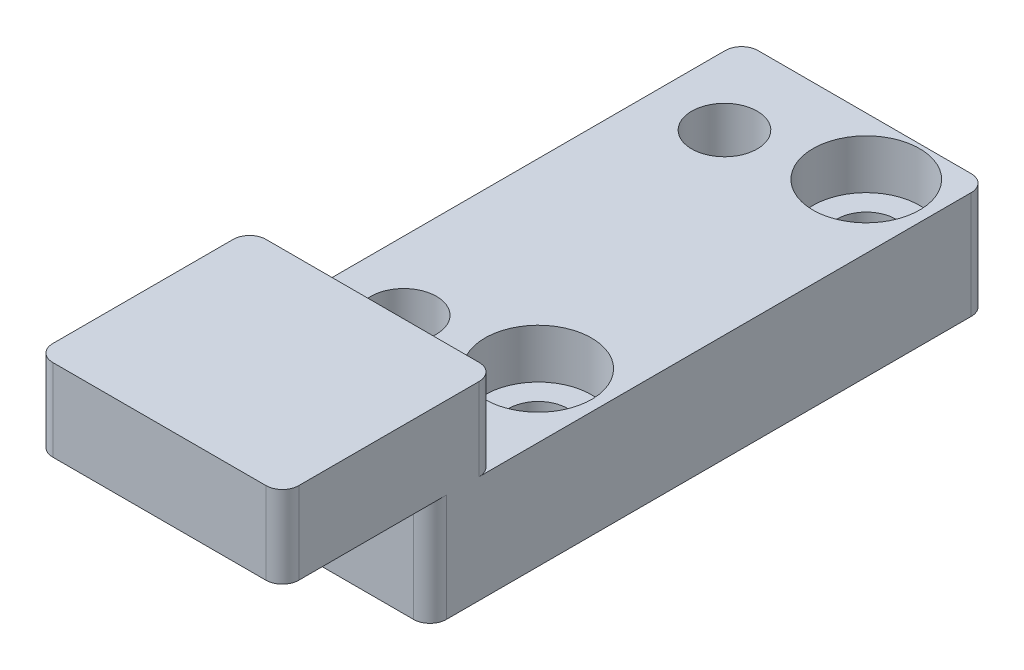
SolidWorks part; units mm, degrees
material "ABS"
ref_plane "Front Plane" through (0, 0, 0) normal (0, 0, 1) x (1, 0, 0)
ref_plane "Top Plane" through (0, 0, 0) normal (0, 1, 0) x (1, 0, 0)
ref_plane "Right Plane" through (0, 0, 0) normal (1, 0, 0) x (0, 0, -1)
sketch "Sketch1" plane through (0, 0, 0) normal (0, 0, 1) x (1, 0, 0)
  line L1 (0, 0) -> (15, 0)
  line L2 (0, 0) -> (0, 6.539)
  line L3 (0, 6.539) -> (15, 6.539)
  line L4 (15, 0) -> (15, 6.539)
  dimension "D1" = 15
  dimension "D2" = 6.539
extrude "Boss-Extrude1" add sketch "Sketch1" along normal blind 30
hole_wizard "CBORE for M3 SHCS1" positions "Sketch2" profile "Sketch3" counterbore size "M3" standard "ANSI Metric" end condition through all
sketch "Sketch2" plane through (0, 6.539, 0) normal (0, 1, 0) x (1, 0, 0)
  point P0 (11.1, -3.5)
  point P3 (11.1, -23.5)
sketch "Sketch3" plane through (11.1, 6.539, 3.5) normal (1, 0, 0) x (0, 0, 1)
  line L0 (0, 0) -> (0, 6.539)
  line L1 (0, 6.539) -> (1.8, 6.539)
  line L3 (1.8, 6.539) -> (1.8, 3)
  line L4 (1.8, 3) -> (3.25, 3)
  line L5 (3.25, 3) -> (3.25, 0)
  line L7 (3.25, 0) -> (0, 0)
  line L11 (0, -6.35) -> (0, 107.95) construction
  dimension "Thru Hole Dia." = 3.6
  dimension "Thru Hole Depth" = 6.539
  dimension "C'Bore Dia." = 6.5
  dimension "C'Bore Depth" = 3
hole_wizard "CBORE for #6 Socket Head Cap Screw1" positions "Sketch4" profile "Sketch5" counterbore size "#6" standard "ANSI Inch" end condition up to next
sketch "Sketch4" plane through (0, 0, 0) normal (0, -1, 0) x (-1, 0, 0)
  point P0 (-4.175, -24.779)
  point P3 (-4.175, -5.221)
sketch "Sketch5" plane through (4.175, 0, 24.779) normal (1, 0, 0) x (0, 0, -1)
  line L0 (0, 0) -> (0, 6.539)
  line L1 (0, 6.539) -> (1.9987, 6.539)
  line L3 (1.9987, 6.539) -> (1.9987, 3.5052)
  line L4 (1.9987, 3.5052) -> (3.5725, 3.5052)
  line L5 (3.5725, 3.5052) -> (3.5725, 0)
  line L7 (3.5725, 0) -> (0, 0)
  line L11 (0, -6.35) -> (0, 107.95) construction
  dimension "Thru Hole Dia." = 3.9973
  dimension "Thru Hole Depth" = 6.539
  dimension "C'Bore Dia." = 7.145
  dimension "C'Bore Depth" = 3.5052
sketch "Sketch6" plane through (0, 0, 0) normal (-1, 0, 0) x (0, 0, 1)
  line L0 (30, 0) -> (34, 0)
  line L1 (30, 6.539) -> (30, 0) construction
  line L2 (34, 0) -> (34, 6.569)
  line L3 (34, 6.569) -> (43, 6.569)
  line L4 (43, 6.569) -> (43, 11.569)
  line L5 (43, 11.569) -> (30, 11.569)
  line L6 (30, 11.569) -> (30, 0)
extrude "Boss-Extrude2" add sketch "Sketch6" against normal up to surface (15 mm away) up to face at (15, 3.2695, 15)
fillet "Fillet1" radius 1 8 edges at (0, 3.2695, 0) (15, 9.054, 30) (0, 9.054, 30) (15, 3.2695, 0) (15, 3.2845, 34) (0, 3.2845, 34) (15, 9.069, 43) (0, 9.069, 43)
